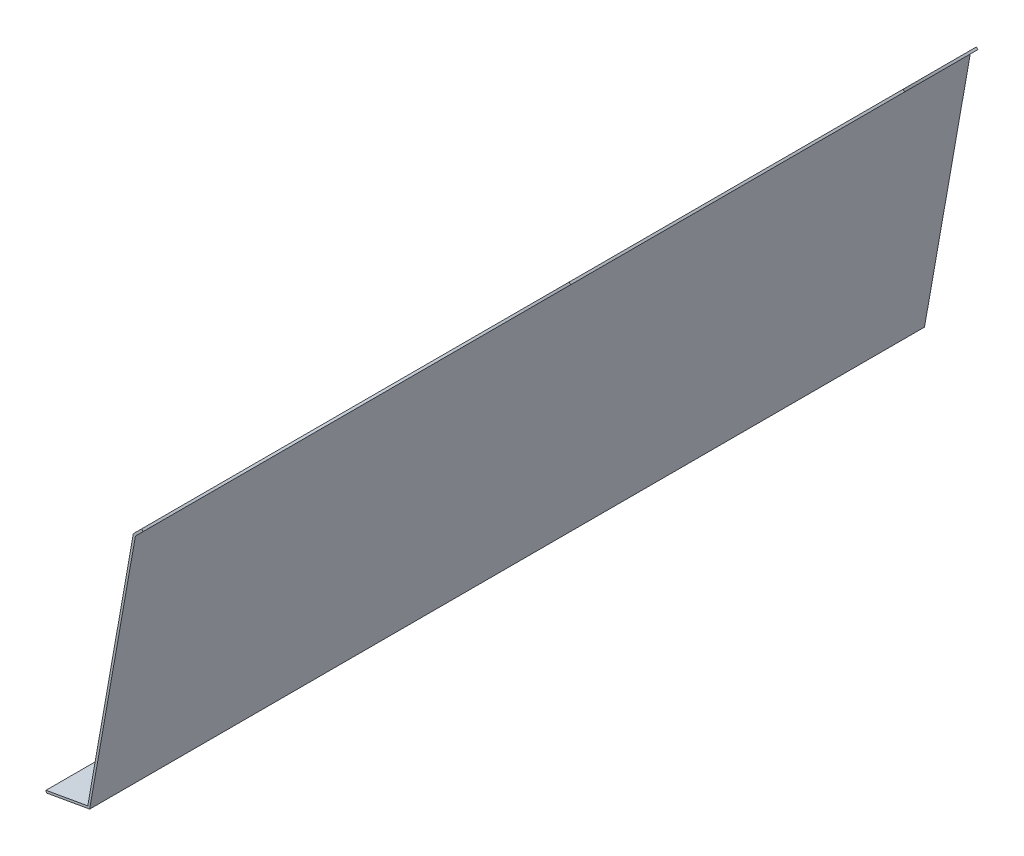
SolidWorks part; units mm, degrees
ref_plane "前视基准面" through (0, 0, 0) normal (0, 0, 1) x (1, 0, 0)
ref_plane "上视基准面" through (0, 0, 0) normal (0, 1, 0) x (1, 0, 0)
ref_plane "右视基准面" through (0, 0, 0) normal (1, 0, 0) x (0, 0, -1)
sketch "草图1" plane through (0, 0, 0) normal (0, 0, 1) x (1, 0, 0)
  line L0 (-27.252, 6.8177) -> (-111.3941, -77.3245)
  line L1 (-111.3941, -77.3245) -> (-132.2117, -195.387)
  line L2 (-132.2117, -195.387) -> (-151.9079, -198.8599)
  line L3 (-45.6367, -31.3661) -> (-55.5362, -21.4666)
  line L4 (-54.4756, -22.5273) -> (-40.3334, -8.3851)
  line L5 (-31.4946, -17.224) -> (-45.6367, -31.3661)
  line L6 (-54.4756, -22.5273) -> (-50.9401, -26.0628)
  line L7 (-38.5657, -24.295) -> (-48.4652, -14.3955)
  line L8 (-31.4946, -17.224) -> (-41.3941, -7.3245)
  line L9 (-73.921, -59.6504) -> (-83.8205, -49.7509)
  line L10 (-82.7599, -50.8115) -> (-68.6177, -36.6694)
  line L11 (-59.7789, -45.5082) -> (-73.921, -59.6504)
  line L12 (-66.85, -52.5793) -> (-76.7494, -42.6798)
  line L13 (-59.7789, -45.5082) -> (-69.6784, -35.6087)
  line L14 (-69.6784, -35.6087) -> (-83.8205, -49.7509)
  line L15 (-133.0749, -194.5237) -> (-152.0815, -197.8751)
  line L16 (-132.2117, -195.387) -> (-122.2117, -195.387)
  line L17 (-27.9591, 7.5248) -> (-112.3242, -76.8403)
  line L18 (-112.3242, -76.8403) -> (-133.0749, -194.5237)
  line L19 (-27.9591, 7.5248) -> (-27.252, 6.8177)
  line L20 (-152.0815, -197.8751) -> (-151.9079, -198.8599)
  line L21 (-132.3854, -194.4021) -> (-152.0815, -197.8751) construction
  line L22 (-112.3242, -76.8403) -> (-133.1965, -195.2133) construction
  circle A0 centre (-45.2832, -26.0628) radius 1.5
  circle A1 centre (-36.7979, -17.5775) radius 1.5
  circle A2 centre (-73.5675, -54.3471) radius 1.5
  circle A3 centre (-65.0822, -45.8618) radius 1.5
  dimension "D1" = 10
  dimension "D2" = 1
extrude "凸台-拉伸1" add sketch "草图1" along normal blind 380 contours L15 L20 L2 L1 L0 L19 L17 L18
sketch "草图2" plane through (-17.0348, 17.0348, 0) normal (0.7071, -0.7071, 0) x (0, 0, -1)
  line L0 (-190, -14.4492) -> (-190, -133.4442)
  line L1 (-380, -14.4492) -> (0, -14.4492) construction
  line L2 (-380, -133.4442) -> (0, -133.4442) construction
  line L3 (-266, -14.4492) -> (-380, -14.4492)
  line L4 (-380, -14.4492) -> (-380, -128.4492)
  line L5 (-114, -14.4492) -> (0, -14.4492)
  line L6 (0, -14.4492) -> (0, -128.4492)
  circle A0 centre (-254.5, -38.4492) radius 1.5
  circle A1 centre (-254.5, -50.4492) radius 1.5
  circle A2 centre (-125.5, -50.4492) radius 1.5
  circle A3 centre (-125.5, -38.4492) radius 1.5
  circle A4 centre (-254.5, -78.4492) radius 1.5
  circle A5 centre (-254.5, -90.4492) radius 1.5
  circle A6 centre (-125.5, -90.4492) radius 1.5
  circle A7 centre (-125.5, -78.4492) radius 1.5
  circle A8 centre (-380, -14.4492) radius 114
  circle A9 centre (0, -14.4492) radius 114
  line M1 (0, -133.4442) -> (0, -14.4492)
  line M2 (0, -14.4492) -> (-380, -14.4492)
  line M3 (-380, -14.4492) -> (-380, -133.4442)
  dimension "D2" = 3
  dimension "D3" = 24
  dimension "D4" = 3
  dimension "D5" = 12
  dimension "D6" = 3
  dimension "D7" = 28
  dimension "D8" = 3
  dimension "D9" = 12
  dimension "D10" = 228
  dimension "D1" = 64.5
extrude "切除-拉伸1" cut sketch "草图2" against normal blind 3 contours A0 | A1 | A8 M3 M2 | A9 M1 M2 | A3 | A2 | A7 | A6 | A5 | A4
